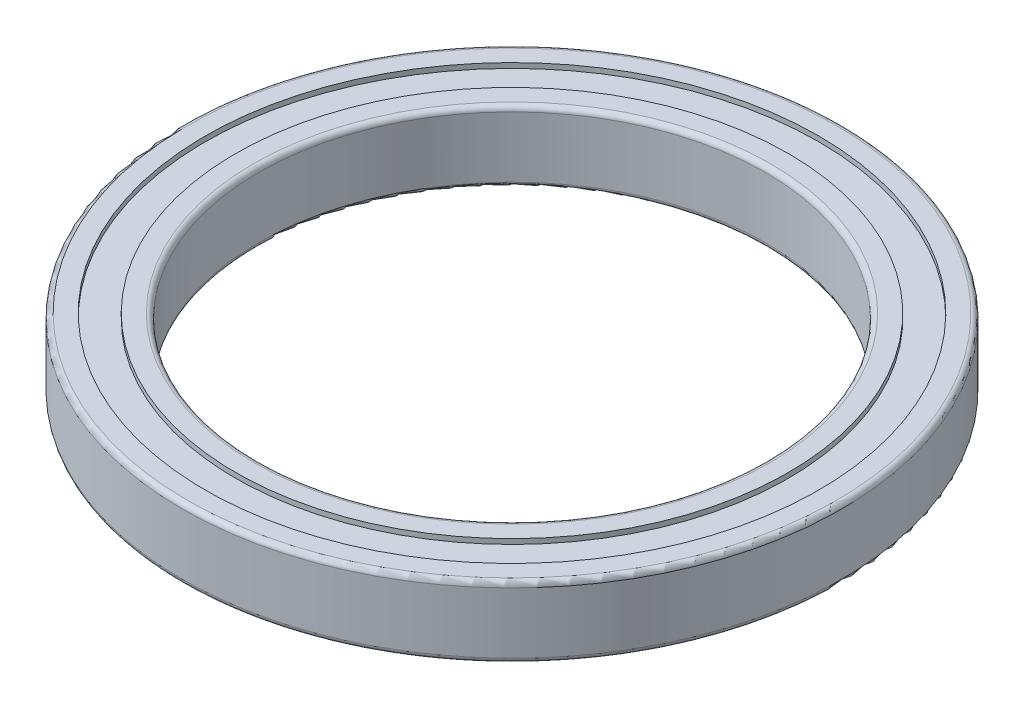
SolidWorks part; units mm, degrees
ref_plane "Ebene vorne" through (0, 0, 0) normal (0, 0, 1) x (1, 0, 0)
ref_plane "Ebene oben" through (0, 0, 0) normal (0, 1, 0) x (1, 0, 0)
ref_plane "Ebene rechts" through (0, 0, 0) normal (1, 0, 0) x (0, 0, -1)
sketch "Skizze1" plane through (0, 0, 0) normal (0, 0, 1) x (1, 0, 0)
  line L0 (0, 0) -> (0, 42.8186) construction
  line L1 (25, 0) -> (27.25, 0)
  line L2 (27.25, 0) -> (27.25, 0.5)
  line L3 (27.25, 0.5) -> (30.25, 0.5)
  line L4 (30.25, 0.5) -> (30.25, 0)
  line L5 (30.25, 0) -> (32.5, 0)
  line L6 (32.5, 0) -> (32.5, 7)
  line L7 (32.5, 7) -> (30.25, 7)
  line L8 (30.25, 7) -> (30.25, 6.5)
  line L9 (30.25, 6.5) -> (27.25, 6.5)
  line L10 (27.25, 6.5) -> (27.25, 7)
  line L11 (27.25, 7) -> (25, 7)
  line L12 (25, 7) -> (25, 0)
  point P15 (31.375, 7)
  dimension "D1" = 50
  dimension "D2" = 65
  dimension "D3" = 60.5
  dimension "D4" = 54.5
  dimension "D5" = 0.5
  dimension "D6" = 0.5
  dimension "D7" = 7
revolve "Rotation1" add sketch "Skizze1" angle 360 about L0
fillet "Verrundung1" radius 0.5 4 edges at (0, 0, -32.5) (0, 7, -32.5) (0, 0, -25) (0, 7, -25)
